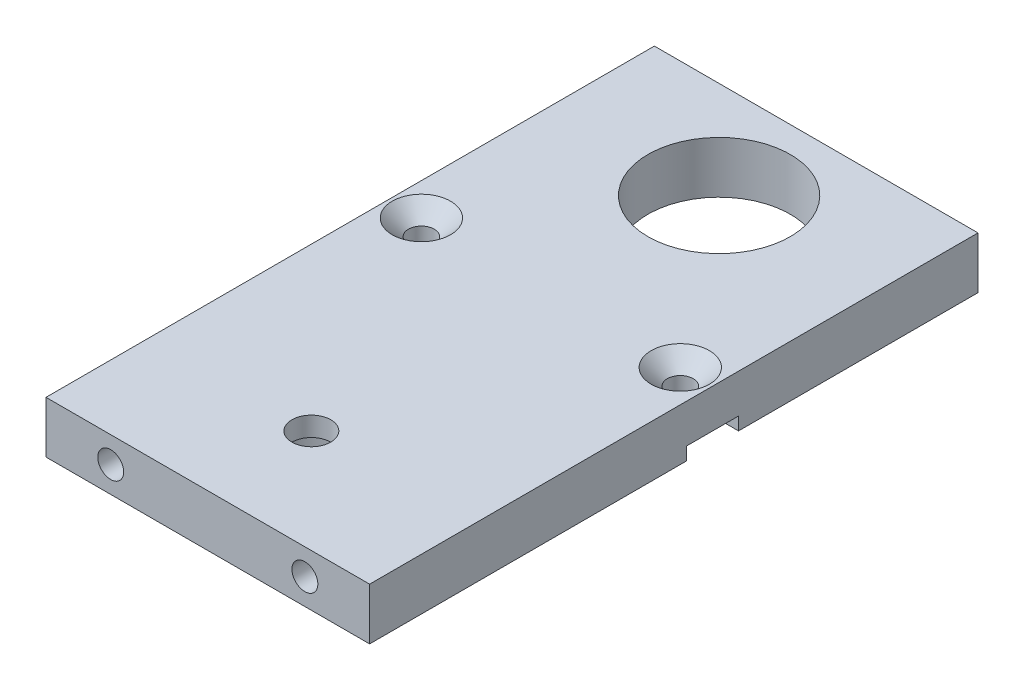
SolidWorks part; units mm, degrees
material "PVC rigide"
ref_plane "Plan de face" through (0, 0, 0) normal (0, 0, 1) x (1, 0, 0)
ref_plane "Plan de dessus" through (0, 0, 0) normal (0, 1, 0) x (1, 0, 0)
ref_plane "Plan de droite" through (0, 0, 0) normal (1, 0, 0) x (0, 0, -1)
sketch "Esquisse1" plane through (0, 0, 0) normal (0, 1, 0) x (1, 0, 0)
  line L0 (-6.4914, -72.1179) -> (-6.4914, 21.8821) construction
  line L1 (-31.4914, 21.8821) -> (18.5086, 21.8821)
  line L2 (-31.4914, 21.8821) -> (-31.4914, -72.1179)
  line L3 (-31.4914, -72.1179) -> (18.5086, -72.1179)
  line L4 (18.5086, 21.8821) -> (18.5086, -72.1179)
  line L6 (-41.3411, -19.1179) -> (33.4874, -19.1179) construction
  circle A1 centre (-6.4914, 6.8821) radius 11
  circle A2 centre (-26.4914, -19.1179) radius 2
  circle A3 centre (13.5086, -19.1179) radius 2
  dimension "D5" = 22
  dimension "D10" = 4
  dimension "D1" = 50
  dimension "D2" = 94
  dimension "D6" = 15
  dimension "D7" = 53
  dimension "D8" = 5
  dimension "D9" = 5
extrude "Boss.-Extru.1" add sketch "Esquisse1" along normal blind 8
chamfer "Chanfrein1" distance 2.5 angle 45 2 edges at (13.5086, 8, 21.1179) (-26.4914, 8, 21.1179)
sketch "Esquisse2" plane through (0, 0, 72.1179) normal (0, 0, 1) x (1, 0, 0)
  line L0 (-31.4914, 4) -> (18.5086, 4) construction
  line L1 (-31.4914, 8) -> (-31.4914, 0) construction
  line L2 (18.5086, 8) -> (18.5086, 0) construction
  circle A0 centre (-21.4914, 4) radius 2
  circle A1 centre (8.5086, 4) radius 2
  dimension "D1" = 4
  dimension "D2" = 10
  dimension "D3" = 10
extrude "Enlèv. mat.-Extru.1" cut sketch "Esquisse2" against normal blind 10
sketch "Esquisse3" plane through (0, 0, 0) normal (0, -1, 0) x (1, 0, 0)
  line L0 (-31.4914, 56.1179) -> (18.5086, 56.1179) construction
  line L1 (-31.4914, -21.8821) -> (-31.4914, 72.1179) construction
  line L2 (18.5086, 72.1179) -> (18.5086, -21.8821) construction
  line L3 (-31.4914, 72.1179) -> (18.5086, 72.1179) construction
  circle A0 centre (-6.4914, 56.1179) radius 8
  dimension "D2" = 16
  dimension "D1" = 16
extrude "Enlèv. mat.-Extru.2" cut sketch "Esquisse3" against normal blind 5
sketch "Esquisse4" plane through (0, 5, 0) normal (0, -1, 0) x (1, 0, 0)
  circle A0 centre (-6.4914, 56.1179) radius 3
  circle A1 centre (-6.4914, 56.1179) radius 8 construction
  dimension "D1" = 6
extrude "Enlèv. mat.-Extru.3" cut sketch "Esquisse4" against normal through all
sketch "Esquisse5" plane through (0, 0, 0) normal (0, -1, 0) x (1, 0, 0)
  line L0 (18.5086, 72.1179) -> (18.5086, -21.8821) construction
  line L1 (18.5086, 15.1179) -> (-31.4914, 15.1179)
  line L2 (18.5086, 15.1179) -> (18.5086, 23.1179)
  line L3 (18.5086, 23.1179) -> (-31.4914, 23.1179)
  line L4 (-31.4914, 15.1179) -> (-31.4914, 23.1179)
  circle A0 centre (13.5086, 19.1179) radius 2 construction
  dimension "D1" = 4
  dimension "D2" = 8
extrude "Enlèv. mat.-Extru.4" cut sketch "Esquisse5" against normal blind 2
